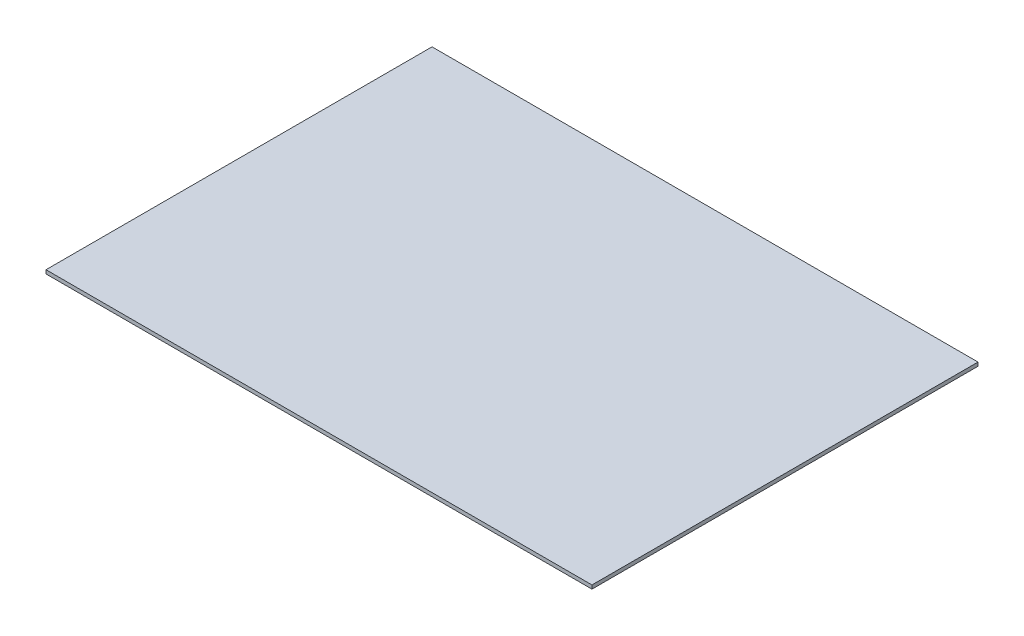
SolidWorks part; units mm, degrees
ref_plane "Front Plane" through (0, 0, 0) normal (0, 0, 1) x (1, 0, 0)
ref_plane "Top Plane" through (0, 0, 0) normal (0, 1, 0) x (1, 0, 0)
ref_plane "Right Plane" through (0, 0, 0) normal (1, 0, 0) x (0, 0, -1)
sketch "Sketch1" plane through (0, 0, 0) normal (0, 1, 0) x (1, 0, 0)
  line L1 (-148.5, -105) -> (148.5, -105)
  line L2 (-148.5, -105) -> (-148.5, 105)
  line L3 (-148.5, 105) -> (148.5, 105)
  line L4 (148.5, -105) -> (148.5, 105)
  line L5 (-148.5, -105) -> (148.5, 105) construction
  line L6 (-148.5, 105) -> (148.5, -105) construction
  point P0 (0, 0)
  dimension "D1" = 297
  dimension "D2" = 210
extrude "Boss-Extrude1" add sketch "Sketch1" along normal blind 2 contours L3 L4 L1 L2
equation "\"l\"= 297"
equation "\"w\"= 210mm"
equation "\"D1@Sketch1\"=\"l\""
equation "\"D2@Sketch1\"=\"w\""
